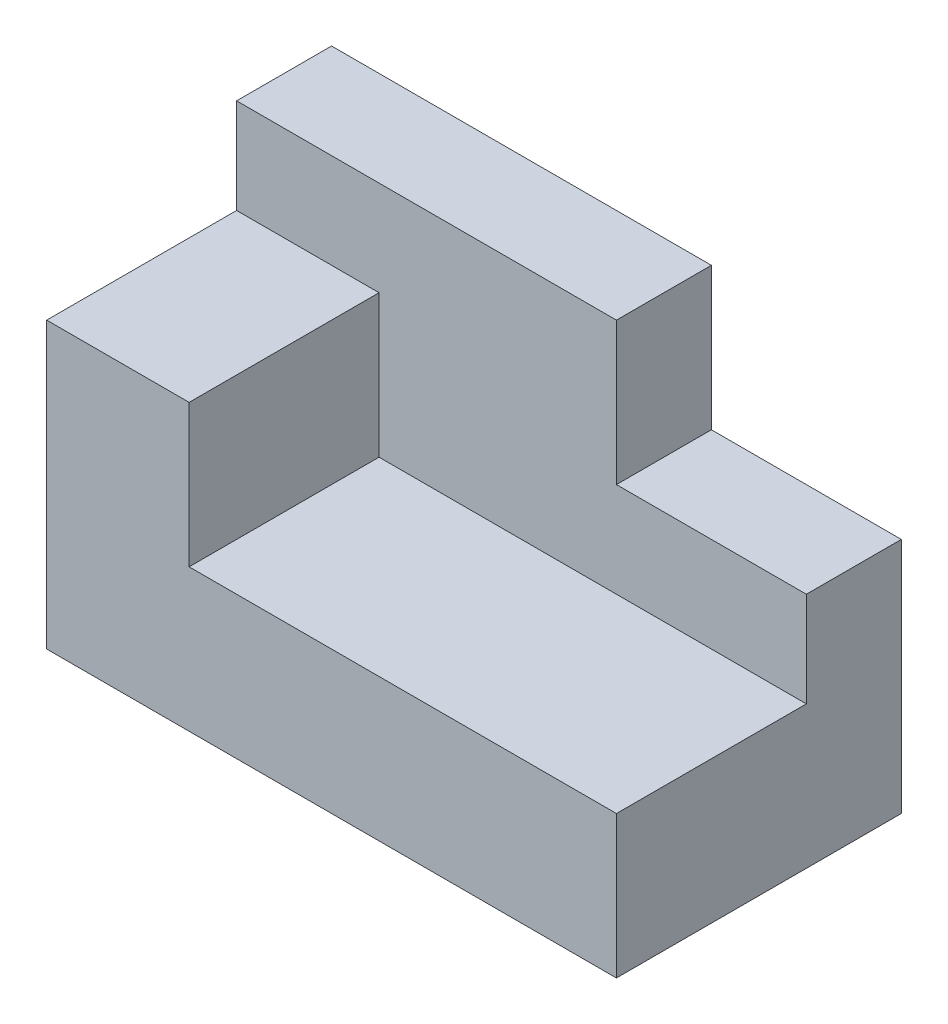
SolidWorks part; units mm, degrees
ref_plane "Plano frontal" through (0, 0, 0) normal (0, 0, 1) x (1, 0, 0)
ref_plane "Plano superior" through (0, 0, 0) normal (0, 1, 0) x (1, 0, 0)
ref_plane "Plano direito" through (0, 0, 0) normal (1, 0, 0) x (0, 0, -1)
sketch "Esboço1" plane through (0, 0, 0) normal (0, 0, 1) x (1, 0, 0)
  line L0 (0, 0) -> (0, 40)
  line L1 (0, 40) -> (40, 40)
  line L2 (40, 40) -> (40, 25)
  line L3 (40, 25) -> (60, 25)
  line L4 (60, 25) -> (60, 0)
  line L5 (60, 0) -> (0, 0)
  dimension "D1" = 40
  dimension "D2" = 40
  dimension "D3" = 25
  dimension "D4" = 60
extrude "Ressalto-extrusão1" add sketch "Esboço1" along normal blind 30
sketch "Esboço2" plane through (0, 40, 0) normal (0, 1, 0) x (1, 0, 0)
  line L1 (40, -10) -> (60, -10)
  line L2 (40, -30) -> (40, 0) construction
  line L3 (60, -30) -> (60, 0) construction
  line L4 (60, 0) -> (40, 0) construction
  line L5 (40, -10) -> (0, -10)
  line L6 (15, -10) -> (15, -30)
  line L7 (40, -30) -> (0, -30) construction
  line L8 (15, -30) -> (60, -30)
  line L9 (60, -30) -> (60, -10)
  line L10 (40, -10) -> (40, 0)
  line L11 (40, 0) -> (60, 0)
  line L12 (60, 0) -> (60, -10)
  line M5 (0, -30) -> (40, -30)
  line M6 (40, -30) -> (40, 0)
  dimension "D1" = 10
  dimension "D2" = 45
extrude "Corte-extrusão1" cut sketch "Esboço2" against normal blind 25 contours L5 L6 M5 M6
sketch "Esboço3" plane through (0, 25, 0) normal (0, 1, 0) x (1, 0, 0)
  line L0 (40, -10) -> (60, -10)
  line L1 (60, -30) -> (60, 0) construction
  line L2 (60, -10) -> (60, -30)
  line L3 (60, -30) -> (40, -30)
  line L4 (15, -30) -> (40, -30) construction
  line L5 (40, -30) -> (40, -10) construction
  line L6 (40, -30) -> (40, -10)
extrude "Corte-extrusão2" cut sketch "Esboço3" against normal blind 10
sketch "Esboço4" plane through (0, 40, 0) normal (0, 1, 0) x (1, 0, 0)
  line L0 (15, -10) -> (0, -10)
  line L1 (0, -30) -> (0, 0) construction
  line L2 (0, -10) -> (0, -30)
  line L3 (0, -30) -> (15, -30)
  line L4 (15, -30) -> (15, -10)
extrude "Corte-extrusão3" cut sketch "Esboço4" against normal blind 10
